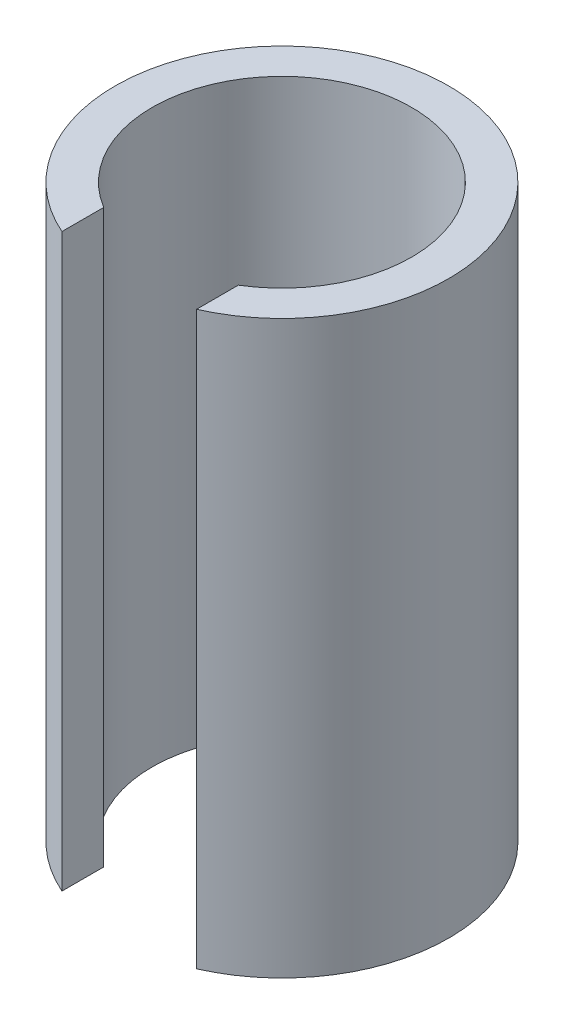
SolidWorks part; units mm, degrees
ref_plane "Plan de face" through (0, 0, 0) normal (0, 0, 1) x (1, 0, 0)
ref_plane "Plan de dessus" through (0, 0, 0) normal (0, 1, 0) x (1, 0, 0)
ref_plane "Plan de droite" through (0, 0, 0) normal (1, 0, 0) x (0, 0, -1)
sketch "Esquisse1" plane through (0, 0, 0) normal (0, 1, 0) x (1, 0, 0)
  circle A0 centre (0, 0) radius 20.45
  circle A1 centre (0, 0) radius 15.9
  dimension "D1" = 40.9
  dimension "D2" = 31.8
extrude "Tube" add sketch "Esquisse1" along normal blind 70
sketch "Esquisse2" plane through (0, 70, 0) normal (0, 1, 0) x (1, 0, 0)
  line L1 (-8.25, -11.6214) -> (8.25, -11.6214)
  line L2 (-8.25, -11.6214) -> (-8.25, -21.9162)
  line L3 (-8.25, -21.9162) -> (8.25, -21.9162)
  line L4 (8.25, -11.6214) -> (8.25, -21.9162)
  dimension "D1" = 8.25
  dimension "D2" = 8.25
extrude "Fente" cut sketch "Esquisse2" against normal through all
